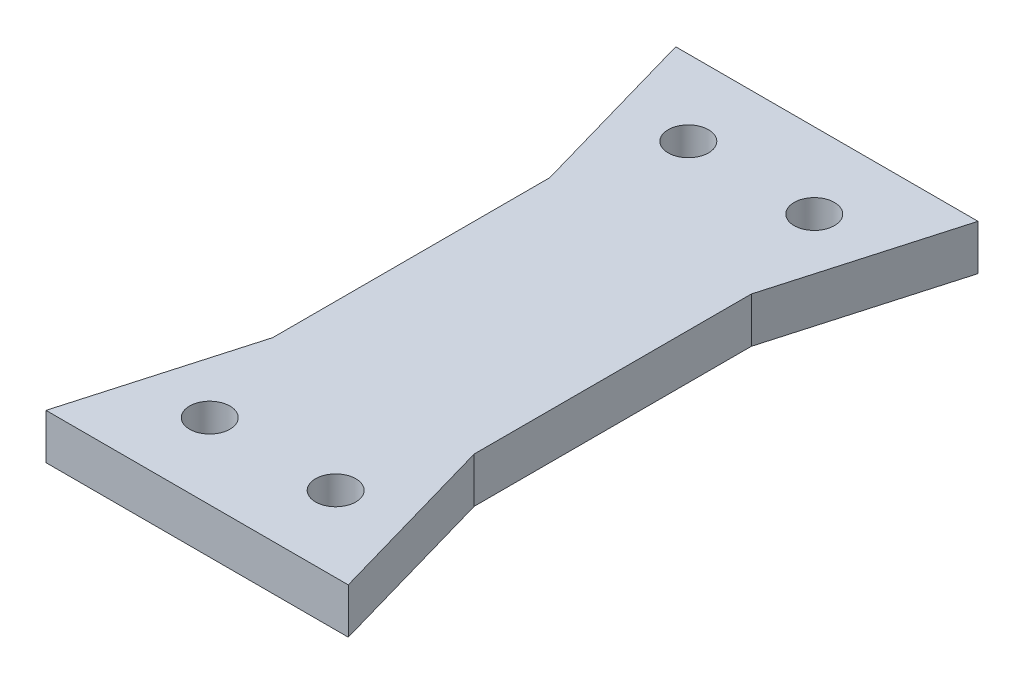
SolidWorks part; units mm, degrees
ref_plane "Front Plane" through (0, 0, 0) normal (0, 0, 1) x (1, 0, 0)
ref_plane "Top Plane" through (0, 0, 0) normal (0, 1, 0) x (1, 0, 0)
ref_plane "Right Plane" through (0, 0, 0) normal (1, 0, 0) x (0, 0, -1)
sketch "Sketch1" plane through (0, 0, 0) normal (0, 1, 0) x (1, 0, 0)
  line L2 (0, 28.6261) -> (0, -32.6516) construction
  line L8 (-57.6033, 0) -> (75.2772, 0) construction
  line L10 (-25, 45) -> (-30, 62.5)
  line L17 (-30, 62.5) -> (30, 62.5)
  line L18 (-25, 45) -> (-20, 27.5)
  line L19 (-20, 27.5) -> (-20, -27.5)
  line L20 (20, 27.5) -> (20, -27.5)
  line L21 (25, 45) -> (20, 27.5)
  line L22 (25, 45) -> (30, 62.5)
  line L23 (25, -45) -> (30, -62.5)
  line L24 (25, -45) -> (20, -27.5)
  line L25 (-25, -45) -> (-20, -27.5)
  line L26 (-30, -62.5) -> (30, -62.5)
  line L27 (-25, -45) -> (-30, -62.5)
  circle A0 centre (-12.5, 47.5) radius 4
  circle A4 centre (12.5, 47.5) radius 4
  circle A5 centre (12.5, -47.5) radius 4
  circle A6 centre (-12.5, -47.5) radius 4
  point P16 (0, 62.5)
  point P19 (0, 62.5)
  point P26 (20, 0)
  point P27 (-20, 0)
  point P29 (0, -62.5)
  dimension "D5" = 8
  dimension "D6" = 17.5
  dimension "D7" = 12.5
  dimension "D3" = 15
  dimension "D1" = 30
  dimension "D2" = 62.5
  dimension "D4" = 25
  dimension "D8" = 35
  dimension "D9" = 20
extrude "Boss-Extrude1" add sketch "Sketch1" along normal blind 9
